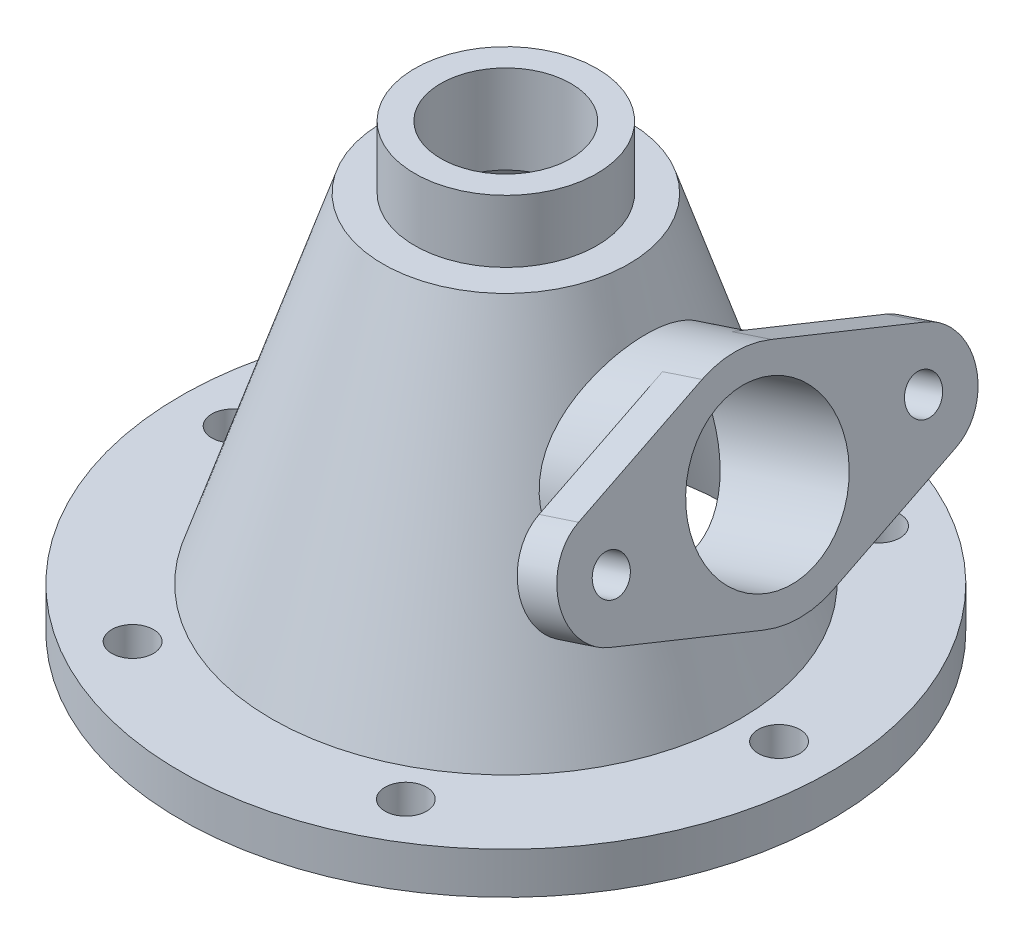
SolidWorks part; units mm, degrees
ref_plane "前视基准面" through (0, 0, 0) normal (0, 0, 1) x (1, 0, 0)
ref_plane "上视基准面" through (0, 0, 0) normal (0, 1, 0) x (1, 0, 0)
ref_plane "右视基准面" through (0, 0, 0) normal (1, 0, 0) x (0, 0, -1)
other "Configuration Table"
sketch "草图1" plane through (0, 0, 0) normal (0, 0, 1) x (1, 0, 0)
  line L0 (42.368, 0) -> (62.5, 0)
  line L1 (62.5, 0) -> (62.5, 8)
  line L2 (62.5, 8) -> (45, 8)
  line L3 (45, 8) -> (23.6189, 73)
  line L4 (23.6189, 73) -> (17.5, 73)
  line L5 (17.5, 73) -> (17.5, 85)
  line L6 (17.5, 85) -> (12.5, 85)
  line L7 (12.5, 85) -> (12.5, 68)
  line L8 (20, 68) -> (42.368, 0)
  line L9 (12.5, 68) -> (20, 68)
  dimension "D1" = 62.5
  dimension "D2" = 8
  dimension "D3" = 17.5
  dimension "D4" = 85
  dimension "D5" = 12
  dimension "D6" = 5
  dimension "D7" = 5
  dimension "D8" = 5
  dimension "D9" = 20
  dimension "D10" = 45
  dimension "D11" = 42.368
sketch "草图3" plane through (0, 0, 0) normal (0, 0, 1) x (1, 0, 0)
  line L0 (0, 0) -> (0, 38.2999) construction
revolve "旋转5" add sketch "草图1" angle 360 about L0
sketch "草图7" plane through (0, 8, 0) normal (0, 1, 0) x (1, 0, 0)
  line L0 (0, 0) -> (52.5, 0) construction
  point P2 (52.5, 0)
  point P10 (52.5, 0)
  dimension "D1" = 52.5
sketch "草图11" plane through (0, 8, 0) normal (0, 1, 0) x (1, 0, 0)
  circle A0 centre (52.5, 0) radius 4
  circle A1 centre (26.25, -45.4663) radius 4
  circle A2 centre (-26.25, -45.4663) radius 4
  circle A3 centre (-52.5, 0) radius 4
  circle A4 centre (-26.25, 45.4663) radius 4
  circle A5 centre (26.25, 45.4663) radius 4
  point P16 (0, 0)
  dimension "D1" = 6
extrude "切除-拉伸1" cut sketch "草图11" against normal blind 10
sketch "草图12" plane through (0, 0, 0) normal (0, 0, 1) x (1, 0, 0)
  line L0 (33.0346, 44.3755) -> (50.1333, 50)
  line L1 (45, 8) -> (23.6189, 73) construction
  line L2 (-62.5, 0) -> (62.5, 0) construction
  dimension "D1" = 18
  dimension "D2" = 50
ref_plane "基准面1" through (50.1333, 50, 0) normal (0.9499, 0.3125, 0) x (0, 0, -1)
sketch "草图13" plane through (50.1333, 50, 0) normal (0.9499, 0.3125, 0) x (0, 0, -1)
  line L0 (0, -31.8312) -> (0, 4.5509) construction
  circle A0 centre (0, -0.4237) radius 20
extrude "凸台-拉伸1" add sketch "草图13" against normal up to surface (18 mm away) contours A0
sketch "草图16" plane through (50.1333, 50, 0) normal (0.9499, 0.3125, 0) x (0, 0, -1)
  line L0 (-33.3333, 9.0104) -> (-6.6629, 18.4338)
  line L1 (-6.6696, -19.2788) -> (-33.3367, -9.8459)
  line L4 (33.3333, 9.0104) -> (6.6629, 18.4338)
  line L5 (6.6696, -19.2788) -> (33.3367, -9.8459)
  arc A0 (-33.3333, 9.0104) -> (-33.3367, -9.8459) centre (-30.0019, -0.4183) ccw
  circle A2 centre (30.0019, -0.4183) radius 3.5
  arc A3 (-6.6696, -19.2788) -> (6.6696, -19.2788) centre (0, -0.4237) ccw
  circle A5 centre (-30.0019, -0.4183) radius 3.5
  arc A6 (33.3367, -9.8459) -> (33.3333, 9.0104) centre (30.0019, -0.4183) ccw
  arc A7 (6.6629, 18.4338) -> (-6.6629, 18.4338) centre (0, -0.4237) ccw
extrude "凸台-拉伸4" add sketch "草图16" against normal blind 8
sketch "草图17" plane through (50.1333, 50, 0) normal (0.9499, 0.3125, 0) x (0, 0, -1)
  line L1 (0, -31.8312) -> (0, 4.5509) construction
  circle A0 centre (0, -0.4183) radius 15
extrude "切除-拉伸2" cut sketch "草图17" against normal up to next
